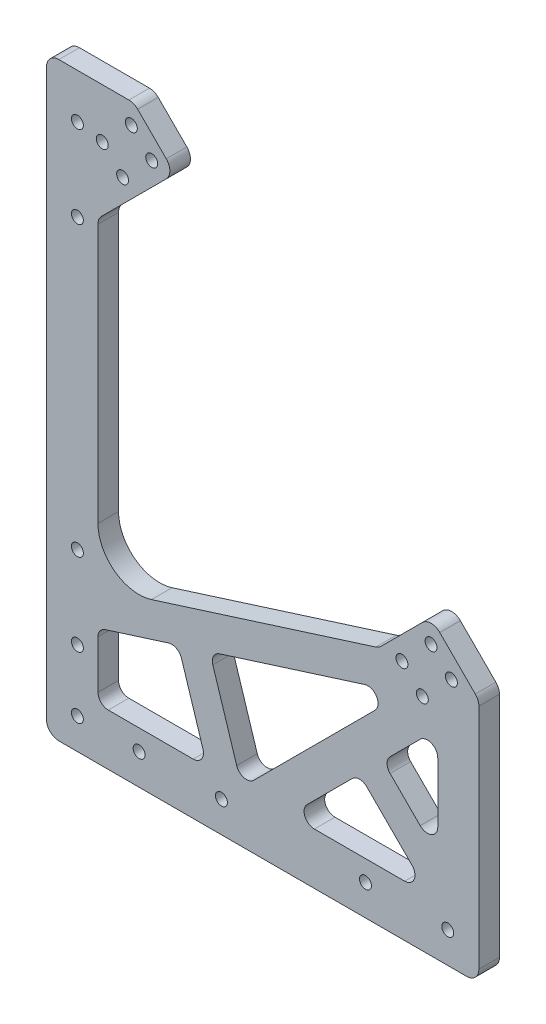
SolidWorks part; units mm, degrees
material "Thornel Mat VMA"
ref_plane "前视基准面" through (0, 0, 0) normal (0, 0, 1) x (1, 0, 0)
ref_plane "上视基准面" through (0, 0, 0) normal (0, 1, 0) x (1, 0, 0)
ref_plane "右视基准面" through (0, 0, 0) normal (1, 0, 0) x (0, 0, -1)
sketch "草图1" plane through (0, 0, 0) normal (0, 0, 1) x (1, 0, 0)
  line L0 (-7.5, -7.5) -> (-7.5, 135.8909)
  line L1 (-7.5, 135.8909) -> (13.766, 135.8909)
  line L2 (13.766, 135.8909) -> (23.7157, 125.9411)
  line L3 (23.7157, 125.9411) -> (5, 107.2254)
  line L4 (5, 107.2254) -> (5, 5)
  line L5 (5, 5) -> (39.9533, 5)
  line L6 (39.9533, 5) -> (79.5772, 44.6238)
  line L7 (79.5772, 44.6238) -> (73.2132, 50.9878)
  line L8 (73.2132, 50.9878) -> (85.9411, 63.7157)
  line L9 (85.9411, 63.7157) -> (122.1569, 27.5)
  line L10 (122.1569, 27.5) -> (122.1569, -7.5)
  line L11 (122.1569, -7.5) -> (-7.5, -7.5)
  line L12 (0, 0) -> (0, 135.8909) construction
  line L13 (0, 0) -> (122.1569, 0) construction
  line L14 (18.0589, 125.9411) -> (10.9878, 118.8701) construction
  line L15 (10.9878, 118.8701) -> (6.0381, 123.8198) construction
  line L16 (6.0381, 123.8198) -> (13.1091, 130.8909) construction
  line L17 (13.1091, 130.8909) -> (18.0589, 125.9411) construction
  line L18 (90.8909, 53.1091) -> (83.8198, 46.0381) construction
  line L19 (83.8198, 46.0381) -> (78.8701, 50.9878) construction
  line L20 (78.8701, 50.9878) -> (85.9411, 58.0589) construction
  line L21 (85.9411, 58.0589) -> (90.8909, 53.1091) construction
  line L22 (18.0589, 125.9411) -> (85.9411, 58.0589) construction
  line L23 (94.5678, 48.018) -> (51.5499, 5)
  line L24 (51.5499, 5) -> (115.1569, 5)
  line L25 (115.1569, 5) -> (115.1569, 27.4289)
  line L26 (115.1569, 27.4289) -> (94.5678, 48.018)
  circle A0 centre (0, 0) radius 1.45
  circle A1 centre (0, 15) radius 1.45
  circle A2 centre (0, 35) radius 1.45
  circle A3 centre (15, 0) radius 1.45
  circle A4 centre (35, 0) radius 1.45
  circle A5 centre (18.0589, 125.9411) radius 1.45
  circle A6 centre (13.1091, 130.8909) radius 1.45
  circle A7 centre (6.0381, 123.8198) radius 1.45
  circle A8 centre (10.9878, 118.8701) radius 1.45
  circle A9 centre (90.8909, 53.1091) radius 1.45
  circle A10 centre (85.9411, 58.0589) radius 1.45
  circle A11 centre (78.8701, 50.9878) radius 1.45
  circle A12 centre (83.8198, 46.0381) radius 1.45
  circle A13 centre (0, 125) radius 1.45
  circle A14 centre (0, 105) radius 1.45
  circle A15 centre (70, 0) radius 1.45
  circle A16 centre (90, 0) radius 1.45
  point P41 (15.584, 128.416)
  point P42 (52, 92)
  dimension "D3" = 2.9
  dimension "D8" = 2.9
  dimension "D13" = 2.9
  dimension "D33" = 70
  dimension "D34" = 20
  dimension "D35" = 35
  dimension "D1" = 7.5
  dimension "D2" = 7.5
  dimension "D4" = 15
  dimension "D5" = 20
  dimension "D6" = 15
  dimension "D7" = 20
  dimension "D9" = 7
  dimension "D10" = 10
  dimension "D11" = 10
  dimension "D12" = 7
  dimension "D14" = 110
  dimension "D15" = 4
  dimension "D16" = 4
  dimension "D17" = 4
  dimension "D18" = 4
  dimension "D19" = 4
  dimension "D20" = 5
  dimension "D21" = 5
  dimension "D22" = 92
  dimension "D23" = 52
  dimension "D24" = 135
  dimension "D25" = 135
  dimension "D26" = 5
  dimension "D27" = 9
  dimension "D28" = 35
  dimension "D29" = 5
  dimension "D30" = 7
  dimension "D31" = 8.2
  dimension "D32" = 20
extrude "凸台-拉伸1" add sketch "草图1" along normal blind 5
sketch "草图3" plane through (0, 0, 0) normal (0, 0, 1) x (1, 0, 0)
  line L0 (97.5678, 45.018) -> (97.5678, 5)
  line L1 (115.1569, 27.4289) -> (94.5678, 48.018) construction
  line L2 (51.5499, 5) -> (115.1569, 5) construction
  line L3 (97.5678, 5) -> (85.5678, 5)
  line L4 (85.5678, 5) -> (68.5588, 22.009)
  line L5 (94.5678, 48.018) -> (51.5499, 5) construction
  line L6 (68.5588, 22.009) -> (74.2157, 27.6658)
  line L7 (74.2157, 27.6658) -> (87.5678, 14.3137)
  line L8 (87.5678, 14.3137) -> (87.5678, 41.018)
  line L9 (87.5678, 41.018) -> (94.5678, 48.018)
  line L10 (94.5678, 48.018) -> (97.5678, 45.018)
  line L11 (73.2132, 50.9878) -> (5, 29.3799)
  line L12 (5, 5) -> (5, 107.2254) construction
  line L13 (5, 29.3799) -> (5, 21)
  line L14 (5, 21) -> (24.5332, 27.1875)
  line L15 (79.5772, 44.6238) -> (73.2132, 50.9878)
  line L16 (73.2132, 50.9878) -> (79.5772, 44.6238) construction
  line L17 (39.9533, 5) -> (32.1597, 29.6034)
  line L19 (24.5332, 27.1875) -> (31.5615, 5)
  line L20 (39.9533, 5) -> (5, 5) construction
  line L21 (31.5615, 5) -> (39.9533, 5)
  line L22 (32.1597, 29.6034) -> (79.5772, 44.6238)
  dimension "D1" = 7
  dimension "D2" = 3
  dimension "D3" = 12
  dimension "D4" = 8
  dimension "D5" = 16
  dimension "D7" = 8
extrude "凸台-拉伸2" add sketch "草图3" along normal up to surface (5 mm away) up to face at (85.2698, 46.0381, 5)
fillet "圆角1" radius 10 1 edges at (5, 29.3799, 2.5)
fillet "圆角2" radius 2.5 17 edges at (115.1569, 5, 2.5) (115.1569, 27.4289, 2.5) (97.5678, 45.018, 2.5) (97.5678, 5, 2.5) (87.5678, 14.3137, 2.5) (87.5678, 41.018, 2.5) (74.2157, 27.6658, 2.5) (51.5499, 5, 2.5) (85.5678, 5, 2.5) (68.5588, 22.009, 2.5) (39.9533, 5, 2.5) (32.1597, 29.6034, 2.5) (24.5332, 27.1875, 2.5) (5, 5, 2.5) (31.5615, 5, 2.5) (5, 21, 2.5) (79.5772, 44.6238, 2.5)
sketch "草图4" plane through (0, 0, 5) normal (0, 0, 1) x (1, 0, 0)
  line L0 (97.5678, -7.5) -> (97.5678, 52.089)
  line L1 (-7.5, -7.5) -> (122.1569, -7.5) construction
  line L2 (122.1569, 27.5) -> (85.9411, 63.7157) construction
  line L3 (97.5678, 52.089) -> (122.1569, 27.5)
  line L4 (122.1569, 27.5) -> (122.1569, -7.5)
  line L5 (122.1569, -7.5) -> (97.5678, -7.5)
  line L6 (97.5678, 38.9824) -> (97.5678, 7.5) construction
extrude "切除-拉伸1" cut sketch "草图4" against normal through all
fillet "圆角3" radius 3 9 edges at (97.5678, 52.089, 2.5) (85.9411, 63.7157, 2.5) (73.2132, 50.9878, 2.5) (5, 107.2254, 2.5) (23.7157, 125.9411, 2.5) (13.766, 135.8909, 2.5) (-7.5, 135.8909, 2.5) (-7.5, -7.5, 2.5) (97.5678, -7.5, 2.5)
